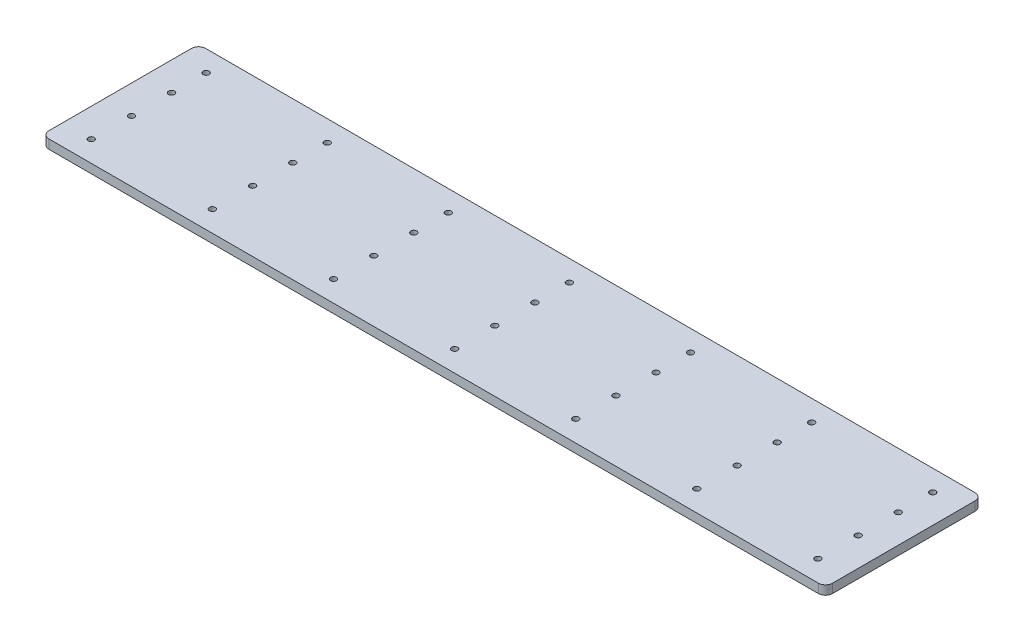
SolidWorks part; units mm, degrees
material "Acrylic (Medium-high impact)"
ref_plane "Front Plane" through (0, 0, 0) normal (0, 0, 1) x (1, 0, 0)
ref_plane "Top Plane" through (0, 0, 0) normal (0, 1, 0) x (1, 0, 0)
ref_plane "Right Plane" through (0, 0, 0) normal (1, 0, 0) x (0, 0, -1)
sketch "Sketch1" plane through (0, 0, 0) normal (0, 1, 0) x (1, 0, 0)
  line L0 (0, 40.299) -> (0, -40.299) construction
  line L1 (-275, 55) -> (275, 55)
  line L2 (-275, 55) -> (-275, -55)
  line L3 (-275, -55) -> (275, -55)
  line L4 (275, 55) -> (275, -55)
  circle A0 centre (0, 40.299) radius 2.5 construction
  circle A1 centre (0, 16.0695) radius 2.5 construction
  circle A2 centre (0, -12.0445) radius 2.5 construction
  circle A3 centre (0, -40.299) radius 2.5 construction
  point P4 (275, 0)
  point P6 (0, 55)
  point P15 (0, 0)
  point P16 (-275, 0)
  dimension "D3" = 5
  dimension "D4" = 24.2295
  dimension "D5" = 28.114
  dimension "D6" = 28.2545
  dimension "D1" = 110
  dimension "D2" = 550
extrude "Boss-Extrude1" add sketch "Sketch1" against normal blind 6.35
hole_wizard "Tap Drill for M5x0.8 Tap1" positions "3DSketch1" profile "Sketch2" hole size "M5x0.8" standard "ANSI Metric" end condition up to next
sketch3d "3DSketch1"
  line L0 (0, 0, -40.299) -> (0, 0, 40.299) construction
  point P0 (0, 0, -40.299)
  point P2 (0, 0, -16.0695)
  point P4 (0, 0, 12.0445)
  point P6 (0, 0, 40.299)
  point P9 (-260, 0, 40.299)
  point P11 (-260, 0, 12.0445)
  point P13 (-260, 0, -15.7199)
  point P16 (-260, 0, -16.0695)
  point P18 (-260, 0, -40.299)
sketch "Sketch2" plane through (0, 0, -40.299) normal (1, 0, 0) x (0, 0, 1)
  line L0 (0, 0) -> (0, 6.35)
  line L1 (0, 6.35) -> (2.1, 6.35)
  line L2 (2.1, 6.35) -> (2.1, 0)
  line L5 (2.1, 0) -> (0, 0)
  line L11 (0, -6.35) -> (0, 107.95) construction
  dimension "Thru Hole Dia." = 4.2
  dimension "Thru Hole Depth" = 6.35
pattern_linear "LPattern1" count 4 spacing 85 along (1, 0, 0) count 4 spacing 85 along (-1, 0, 0) of "Tap Drill for M5x0.8 Tap1"
fillet "Fillet1" radius 5 4 edges at (275, -3.175, -55) (275, -3.175, 55) (-275, -3.175, -55) (-275, -3.175, 55)
